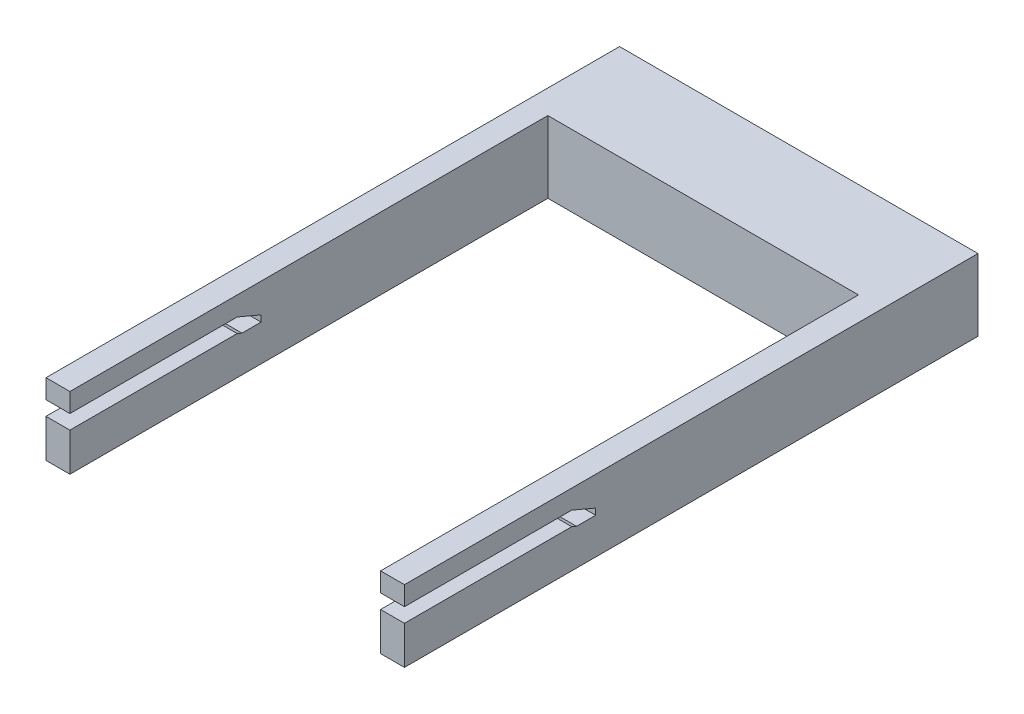
SolidWorks part; units mm, degrees
ref_plane "Front Plane" through (0, 0, 0) normal (0, 0, 1) x (1, 0, 0)
ref_plane "Top Plane" through (0, 0, 0) normal (0, 1, 0) x (1, 0, 0)
ref_plane "Right Plane" through (0, 0, 0) normal (1, 0, 0) x (0, 0, -1)
sketch "Sketch1" plane through (0, 0, 0) normal (0, 1, 0) x (1, 0, 0)
  line L0 (32.5, -60) -> (37.5, -60)
  line L1 (-37.5, 60) -> (37.5, 60)
  line L2 (-37.5, 60) -> (-37.5, -60)
  line L3 (-37.5, -60) -> (-32.5, -60)
  line L4 (37.5, 60) -> (37.5, -60)
  line L5 (-37.5, 60) -> (37.5, -60) construction
  line L6 (-37.5, -60) -> (37.5, 60) construction
  line L7 (-32.5, 40) -> (32.5, 40)
  line L8 (-32.5, 40) -> (-32.5, -60)
  line L10 (32.5, 40) -> (32.5, -60)
  line L11 (-32.5, 40) -> (32.5, -60) construction
  line L12 (-32.5, -60) -> (32.5, 40) construction
  point P0 (0, 0)
  point P6 (0, -10)
  dimension "D1" = 75
  dimension "D2" = 120
  dimension "D3" = 100
  dimension "D4" = 65
extrude "Boss-Extrude1" add sketch "Sketch1" along normal blind 15
sketch "Sketch2" plane through (0, 0, 0) normal (1, 0, 0) x (0, 0, -1)
  line L0 (-60, 11) -> (-25, 11)
  line L1 (-60, 15) -> (-60, 0) construction
  line L2 (-25, 11) -> (-20, 8.8776)
  line L3 (-20, 8.8776) -> (-20, 7.5755)
  line L4 (-20, 7.5755) -> (-24, 7.5755)
  line L5 (-24, 7.5755) -> (-25, 8)
  line L6 (-25, 8) -> (-60, 8)
  line L7 (-60, 8) -> (-60, 11)
  line L9 (-60, 0) -> (60, 0) construction
  dimension "D1" = 3
  dimension "D2" = 35
  dimension "D3" = 23
  dimension "D4" = 40
  dimension "D5" = 4
  dimension "D6" = 8
extrude "Cut-Extrude1" cut sketch "Sketch2" against normal mid plane 75
